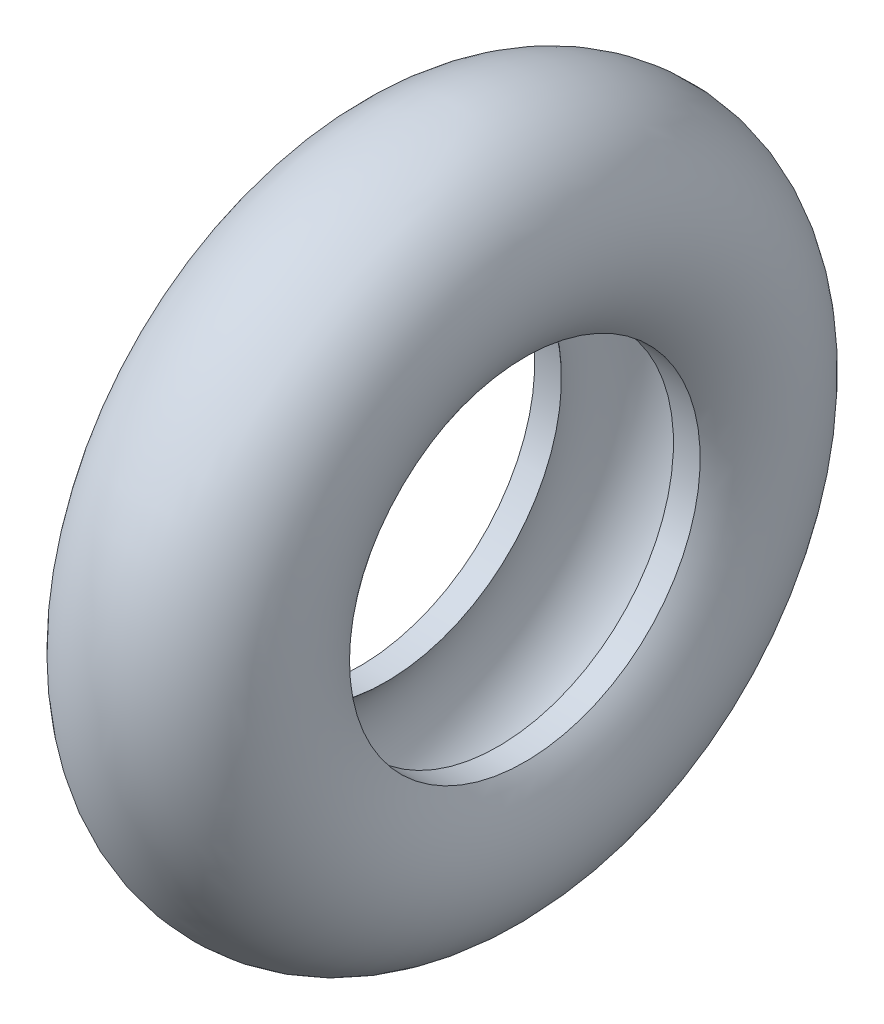
SolidWorks part; units mm, degrees
material "BUTYL"
ref_plane "Plan de face" through (0, 0, 0) normal (0, 0, 1) x (1, 0, 0)
ref_plane "Plan de dessus" through (0, 0, 0) normal (0, 1, 0) x (1, 0, 0)
ref_plane "Plan de droite" through (0, 0, 0) normal (1, 0, 0) x (0, 0, -1)
sketch "Esquisse1" plane through (0, 0, 0) normal (0, 0, 1) x (1, 0, 0)
  line L0 (-106.6081, 0) -> (126.1459, 0) construction
  line L1 (0, 110.4307) -> (0, -134.2158) construction
  line L2 (120.5589, 184.995) -> (-140.6473, 184.995) construction
  line L3 (-43.624, 92.4481) -> (-29.5288, 92.4481)
  line L4 (29.5288, 92.4481) -> (43.624, 92.4481)
  arc A0 (43.624, 92.4481) -> (-43.624, 92.4481) centre (0, 128.44) ccw
  arc A1 (-29.5288, 92.4481) -> (29.5288, 92.4481) centre (0, 128.44) cw
  dimension "D1" = 113.11
  dimension "D5" = 10
  dimension "D2" = 128.44
  dimension "D3" = 184.995
  dimension "D4" = 92.4481
revolve "Révolution1" add sketch "Esquisse1" angle 360 about L0
